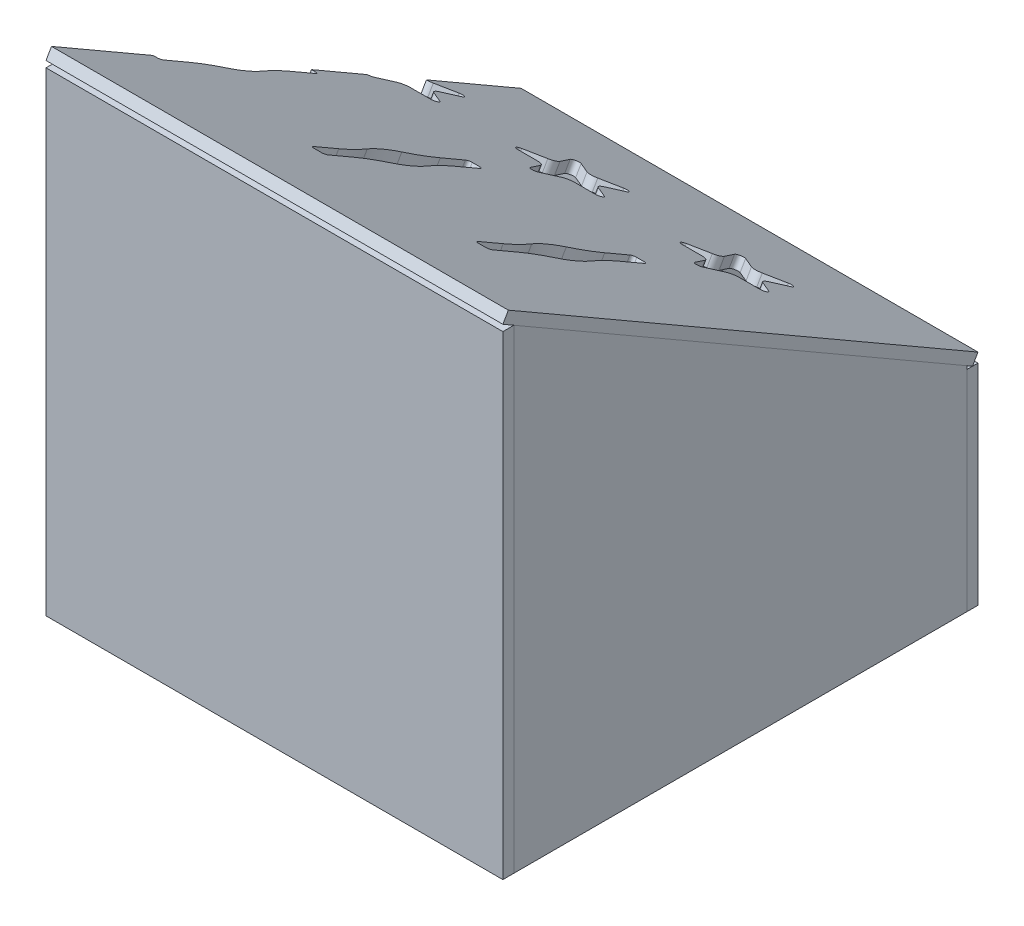
SolidWorks part; units mm, degrees
ref_plane "Plan de face" through (0, 0, 0) normal (0, 0, 1) x (1, 0, 0)
ref_plane "Plan de dessus" through (0, 0, 0) normal (0, 1, 0) x (1, 0, 0)
ref_plane "Plan de droite" through (0, 0, 0) normal (1, 0, 0) x (0, 0, -1)
sketch "repere_profil" plane through (0, 0, 0) normal (1, 0, 0) x (0, 0, -1)
  line L0 (0, 0) -> (-130, 0)
  line L1 (-130, 0) -> (-130, 135.0555)
  line L2 (-130, 135.0555) -> (0, 60)
  line L3 (0, 60) -> (0, 0)
  line L4 (-3, 3) -> (-127, 3)
  line L5 (-127, 3) -> (-127, 129.8594)
  line L6 (-127, 129.8594) -> (-3, 58.2679)
  line L7 (-3, 58.2679) -> (-3, 3)
  line L8 (-127, 129.8594) -> (-130, 131.5914) construction
  line L9 (-130, 131.5914) -> (-128.5, 134.1895) construction
  line L10 (-127, 129.8594) -> (-130, 129.8594) construction
  line L11 (-3, 58.2679) -> (-1.5, 57.4019) construction
  line L12 (-1.5, 57.4019) -> (0, 60) construction
  line L13 (-3, 57.4019) -> (0, 57.4019) construction
  line L14 (-3, 3) -> (-3, 0) construction
  line L15 (-127, 3) -> (-127, 0) construction
  point P15 (0, 0)
  point P18 (0, 0)
  point P19 (0, 0)
  point P20 (0, 0)
  point P21 (0, 0)
  point P22 (0, 0)
  point P23 (0, 0)
  point P24 (0, 0)
  point P25 (0, 0)
  point P26 (0, 0)
  dimension "D2" = 60
  dimension "D3" = 130
  dimension "D4" = 60
  dimension "D1" = 3
sketch "repere_face_panneau" plane through (0, 0, 0) normal (0, 1, 0) x (1, 0, 0)
  line L0 (-122, -140) -> (-90, -140) construction
  line L1 (-90, -140) -> (-45, -140) construction
  line L2 (-45, -140) -> (0, -140) construction
  line L3 (0, -140) -> (45, -140) construction
  line L4 (45, -140) -> (90, -140) construction
  line L5 (90, -140) -> (122, -140) construction
  line L6 (0, -140) -> (0, 0) construction
  line L7 (-122, -140) -> (-125, -140) construction
  line L8 (122, -140) -> (125, -140) construction
  line L9 (-67.5, -140) -> (-67.5, 0) construction
  line L10 (-22.5, -140) -> (-22.5, 0) construction
  line L11 (22.5, -140) -> (22.5, 0) construction
  line L12 (67.5, -140) -> (67.5, 0) construction
  point P19 (0, 0)
  point P20 (0, 0)
  dimension "D1" = 140
  dimension "D2" = 45
  dimension "D3" = 32
  dimension "D4" = 244
  dimension "D5" = 3
ref_plane "Plan_panneau" through (0, 45, -25.9808) normal (0, -0.866, 0.5) x (0, -0.5, -0.866)
ref_plane "Plan_arriere" through (0, 0, 130) normal (0, 0, 1) x (1, 0, 0)
sketch "Esquisse3" plane through (0, 0, 0) normal (0, 1, 0) x (1, 0, 0)
  line L1 (122, -3) -> (0, -3)
  line L2 (122, -3) -> (122, -127)
  line L3 (122, -127) -> (0, -127)
  line L4 (0, -3) -> (0, -127)
extrude "plq_base" add sketch "Esquisse3" along normal blind 3
sketch "Esquisse4" plane through (0, 0, 130) normal (0, 0, 1) x (1, 0, 0)
  line L1 (0, 129.8594) -> (125, 129.8594)
  line L2 (0, 129.8594) -> (0, 0)
  line L3 (0, 0) -> (125, 0)
  line L4 (125, 129.8594) -> (125, 0)
extrude "plq_arriere" add sketch "Esquisse4" against normal blind 3 separate body
sketch "Esquisse5" plane through (0, 0, 0) normal (0, 0, 1) x (1, 0, 0)
  line L1 (0, 57.4019) -> (125, 57.4019)
  line L2 (0, 57.4019) -> (0, 0)
  line L3 (0, 0) -> (125, 0)
  line L4 (125, 57.4019) -> (125, 0)
extrude "plq_avant" add sketch "Esquisse5" along normal blind 3 separate body
sketch "Esquisse6" plane through (0, 45, -25.9808) normal (0, -0.866, 0.5) x (0, -0.5, -0.866)
  line L1 (-178.379, 0) -> (-30, 0)
  line L2 (-178.379, 0) -> (-178.379, 125)
  line L3 (-178.379, 125) -> (-30, 125)
  line L4 (-30, 0) -> (-30, 125)
extrude "plq_panneau (dessus)" add sketch "Esquisse6" along normal blind 3 separate body
sketch "Esquisse7" plane through (0, 0, 0) normal (1, 0, 0) x (0, 0, -1)
  line L0 (-127, 129.8594) -> (-127, 0)
  line L1 (-127, 0) -> (-3, 0)
  line L2 (-3, 0) -> (-3, 58.2679)
  line L3 (-3, 58.2679) -> (-127, 129.8594)
extrude "plq_cote" add sketch "Esquisse7" against normal blind 3 from vertex at 125 separate body starting at point (125, 0, 140)
sketch "Esquisse8" plane through (0, 45, -25.9808) normal (0, -0.866, 0.5) x (0, -0.5, -0.866)
  line L0 (-72.6063, 92.8064) -> (-77.7311, 91.1413)
  line L1 (-77.7311, 88.8587) -> (-72.6063, 87.1936)
  line L2 (-70.8788, 84.8159) -> (-70.8788, 79.4274)
  line L3 (-68.708, 78.722) -> (-65.5407, 83.0815)
  line L4 (-62.7456, 83.9896) -> (-57.6208, 82.3245)
  line L5 (-56.2791, 84.1711) -> (-59.4464, 88.5305)
  line L6 (-59.4464, 91.4695) -> (-56.2791, 95.8289)
  line L7 (-57.6208, 97.6755) -> (-62.7456, 96.0104)
  line L8 (-65.5407, 96.9185) -> (-68.708, 101.278)
  line L9 (-70.8788, 100.5726) -> (-70.8788, 95.1841)
  line L10 (-54.1083, 98.8168) -> (-70.8788, 104.2658) construction
  line L11 (-70.8788, 104.2658) -> (-81.2436, 90) construction
  line L12 (-70.8788, 75.7342) -> (-81.2436, 90) construction
  line L13 (-54.1083, 98.8168) -> (-54.1083, 81.1832) construction
  line L14 (-70.8788, 75.7342) -> (-54.1083, 81.1832) construction
  line L15 (-60.5141, 90) -> (-64.473, 84.5509) construction
  line L16 (-64.473, 84.5509) -> (-70.8788, 86.6323) construction
  line L17 (-70.8788, 86.6323) -> (-70.8788, 93.3677) construction
  line L18 (-70.8788, 93.3677) -> (-64.473, 95.4491) construction
  line L19 (-64.473, 95.4491) -> (-60.5141, 90) construction
  line L20 (-121.2436, 90) -> (-66.2436, 90) construction
  circle A0 centre (-66.2436, 90) radius 5.7295 construction
  circle A1 centre (-66.2436, 90) radius 15 construction
  arc A2 (-59.4464, 88.5305) -> (-59.4464, 91.4695) centre (-57.4239, 90) cw
  arc A3 (-65.5407, 83.0815) -> (-62.7456, 83.9896) centre (-63.5181, 81.612) cw
  arc A4 (-72.6063, 87.1936) -> (-70.8788, 84.8159) centre (-73.3788, 84.8159) cw
  arc A5 (-72.6063, 92.8064) -> (-70.8788, 95.1841) centre (-73.3788, 95.1841) ccw
  arc A6 (-62.7456, 96.0104) -> (-65.5407, 96.9185) centre (-63.5181, 98.388) cw
  arc A7 (-77.7311, 91.1413) -> (-77.7311, 88.8587) centre (-77.3603, 90) ccw
  arc A8 (-70.8788, 79.4274) -> (-68.708, 78.722) centre (-69.6788, 79.4274) ccw
  arc A9 (-57.6208, 82.3245) -> (-56.2791, 84.1711) centre (-57.2499, 83.4658) ccw
  arc A10 (-56.2791, 95.8289) -> (-57.6208, 97.6755) centre (-57.2499, 96.5342) ccw
  arc A11 (-68.708, 101.278) -> (-70.8788, 100.5726) centre (-69.6788, 100.5726) ccw
  dimension "D2" = 30
  dimension "D4" = 2.5
  dimension "D5" = 1.2
  dimension "D3" = 55
extrude "etoile_1" cut sketch "Esquisse8" along normal through all
sketch "Esquisse9" plane through (0, 45, -25.9808) normal (0, -0.866, 0.5) x (0, -0.5, -0.866)
  line L0 (-111.2436, 90) -> (-131.2436, 90) construction
  line L1 (-97.2436, 88) -> (-145.2436, 88)
  line L2 (-96.2436, 89) -> (-96.2436, 91)
  line L3 (-97.2436, 92) -> (-145.2436, 92)
  line L4 (-146.2436, 89) -> (-146.2436, 91)
  line L5 (-96.2436, 88) -> (-146.2436, 92) construction
  line L6 (-96.2436, 92) -> (-146.2436, 88) construction
  arc A0 (-96.2436, 91) -> (-97.2436, 92) centre (-97.2436, 91) ccw
  arc A1 (-97.2436, 88) -> (-96.2436, 89) centre (-97.2436, 89) ccw
  arc A2 (-145.2436, 88) -> (-146.2436, 89) centre (-145.2436, 89) cw
  arc A3 (-145.2436, 92) -> (-146.2436, 91) centre (-145.2436, 91) ccw
  ellipse E0 centre (-121.2436, 90) end of major axis (-131.2436, 90) minor radius 4
  point P0 (-121.2436, 90)
  dimension "D3" = 1
  dimension "D1" = 4
  dimension "D2" = 50
  dimension "D4" = 20
  dimension "D5" = 8
extrude "fente_1" cut sketch "Esquisse9" along normal through all contours E0 | L3 A3 L4 A2 L1 A1 L2 A0
fillet "Congé1" radius 42 4 edges at (88, 108.6529, 87.2692) (88, 99.9926, 72.2692) (92, 108.6529, 87.2692) (92, 99.9926, 72.2692)
pattern_linear "Répétition linéaire2" count 3 spacing 45 along (-1, 0, 0) of "etoile_1", "fente_1", "Congé1"
sketch "Esquisse10" plane through (0, 0, 0) normal (1, 0, 0) x (0, 0, -1)
  line L0 (-127, 129.8594) -> (-127, 3)
  line L1 (-127, 3) -> (-3, 3)
  line L2 (-3, 3) -> (-3, 58.2679)
  line L3 (-3, 58.2679) -> (-11.2372, 63.0237)
  line L4 (-11.2372, 63.0237) -> (-15.2372, 56.0955)
  line L5 (-15.2372, 56.0955) -> (-49.8782, 76.0955)
  line L6 (-120.8923, 117.0955) -> (-116.8923, 124.0237)
  line L7 (-116.8923, 124.0237) -> (-127, 129.8594)
  line L8 (-116.8923, 124.0237) -> (-63.1987, 93.0237) construction
  line L9 (-127, 129.8594) -> (-3, 58.2679) construction
  line L10 (-67.1987, 86.0955) -> (-120.8923, 117.0955)
  line L11 (-49.8782, 76.0955) -> (-67.1987, 86.0955) construction
  line L12 (-63.1987, 93.0237) -> (-45.8782, 83.0237)
  line L13 (-45.8782, 83.0237) -> (-11.2372, 63.0237) construction
  line L14 (-67.1987, 86.0955) -> (-63.1987, 93.0237)
  line L15 (-49.8782, 76.0955) -> (-45.8782, 83.0237)
  line L16 (-127, 109.8594) -> (-130, 109.8594)
  line L17 (-130, 109.8594) -> (-130, 89.8594)
  line L18 (-130, 89.8594) -> (-127, 89.8594)
  line L19 (-127, 43) -> (-130, 43)
  line L20 (-130, 43) -> (-130, 23)
  line L21 (-130, 23) -> (-127, 23)
  line L22 (-107, 3) -> (-107, 0)
  line L23 (-107, 0) -> (-87, 0)
  line L24 (-87, 0) -> (-87, 3)
  line L25 (-43, 3) -> (-43, 0)
  line L26 (-43, 0) -> (-23, 0)
  line L27 (-23, 0) -> (-23, 3)
  line L28 (-3, 12) -> (0, 12)
  line L29 (0, 12) -> (0, 24)
  line L30 (0, 24) -> (-3, 24)
  line L31 (-3, 37.2679) -> (0, 37.2679)
  line L32 (0, 37.2679) -> (0, 49.2679)
  line L33 (0, 49.2679) -> (-3, 49.2679)
  line L34 (-87, 0) -> (-43, 0) construction
  line L35 (-65, 0) -> (-65, 3) construction
  line L36 (0, 37.2679) -> (0, 24) construction
  line L37 (0, 30.634) -> (-3, 30.634) construction
  line L38 (-130, 89.8594) -> (-130, 43) construction
  line L39 (-130, 66.4297) -> (-127, 66.4297) construction
  point P46 (-97, 0)
  point P47 (0, 18)
  point P54 (-130, 33)
  dimension "D1" = 25
  dimension "D2" = 42
  dimension "D3" = 8
  dimension "D4" = 40
  dimension "D5" = 20
  dimension "D6" = 12
  dimension "D7" = 30
  dimension "D8" = 20
  dimension "D9" = 15
  dimension "D10" = 30
extrude "separateur_1" add sketch "Esquisse10" along normal mid plane 3 from vertex at 67.5 separate body contours L5 L15 L12 L14 L10 L6 L7 L0 L1 L2 L3 L4 | L17 L18 L0 L16 | L20 L21 L0 L19 | L23 L24 L1 L22 | L26 L27 L1 L25 | L29 L30 L2 L28 | L32 L33 L2 L31 starting at point (67.5, 0, 140)
equation "\"ep_plexi\"=3"
equation "\"D5@repere_face_panneau\"=\"ep_plexi\""
equation "\"D1@repere_profil\"=\"ep_plexi\""
equation "\"D1@plq_base\"=\"ep_plexi\""
equation "\"D1@plq_arriere\" = \"ep_plexi\""
equation "\"D1@plq_avant\" = \"ep_plexi\""
equation "\"D1@plq_panneau (dessus)\" = \"ep_plexi\""
equation "\"D1@plq_cote\" = \"ep_plexi\""
equation "\"D1@separateur_1\"=\"ep_plexi\""
